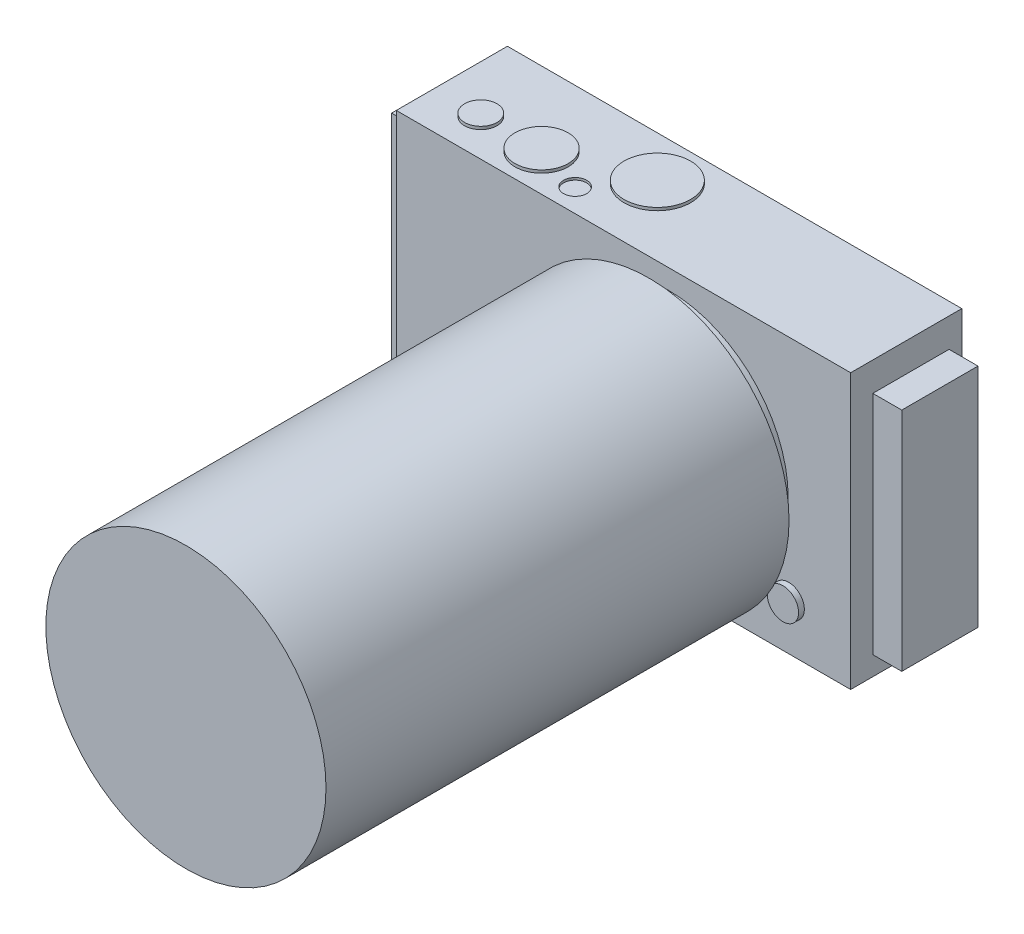
SolidWorks part; units mm, degrees
ref_plane "Front Plane" through (0, 0, 0) normal (0, 0, 1) x (1, 0, 0)
ref_plane "Top Plane" through (0, 0, 0) normal (0, 1, 0) x (1, 0, 0)
ref_plane "Right Plane" through (0, 0, 0) normal (1, 0, 0) x (0, 0, -1)
sketch "Sketch1" plane through (0, 0, 0) normal (0, 0, 1) x (1, 0, 0)
  line L1 (0, 0) -> (99.695, 0)
  line L2 (0, 0) -> (0, 60.198)
  line L3 (0, 60.198) -> (99.695, 60.198)
  line L4 (99.695, 0) -> (99.695, 60.198)
  dimension "D1" = 99.695
  dimension "D2" = 60.198
extrude "Boss-Extrude1" add sketch "Sketch1" along normal blind 24.384
sketch "Sketch2" plane through (0, 0, 24.384) normal (0, 0, 1) x (1, 0, 0)
  line L0 (0, 30.099) -> (99.695, 30.099) construction
  line L1 (0, 60.198) -> (0, 0) construction
  line L2 (99.695, 0) -> (99.695, 60.198) construction
  line L3 (59.7588, 55.88) -> (59.7588, 3.429) construction
  line L4 (99.695, 60.198) -> (0, 60.198) construction
  line L5 (0, 0) -> (99.695, 0) construction
  circle A0 centre (59.7588, 29.6545) radius 26.2255
  point P15 (85.979, 30.1802)
  dimension "D1" = 4.318
  dimension "D2" = 3.429
  dimension "D3" = 13.716
extrude "Boss-Extrude2" add sketch "Sketch2" along normal blind 4.318
sketch "Sketch3" plane through (0, 0, 24.384) normal (0, 0, 1) x (1, 0, 0)
  line L0 (99.695, 0) -> (99.695, 60.198) construction
  line L1 (0, 0) -> (99.695, 0) construction
  circle A0 centre (86.106, 10.16) radius 3.429
  dimension "D1" = 6.858
  dimension "D2" = 13.589
  dimension "D3" = 10.16
extrude "Boss-Extrude3" add sketch "Sketch3" along normal blind 1.27
sketch "Sketch4" plane through (0, 60.198, 0) normal (0, 1, 0) x (1, 0, 0)
  line L0 (0, -24.384) -> (0, 0) construction
  line L1 (99.695, -24.384) -> (0, -24.384) construction
  circle A0 centre (10.414, -16.256) radius 3.556
  circle A1 centre (23.749, -16.256) radius 5.842
  circle A2 centre (42.545, -9.652) radius 7.3025
  dimension "D1" = 7.112
  dimension "D2" = 11.684
  dimension "D3" = 14.605
  dimension "D4" = 10.414
  dimension "D5" = 23.749
  dimension "D6" = 42.545
  dimension "D7" = 8.128
  dimension "D8" = 8.128
  dimension "D9" = 14.732
extrude "Boss-Extrude4" add sketch "Sketch4" along normal blind 0.635
sketch "Sketch7" plane through (0, 60.198, 0) normal (0, 1, 0) x (1, 0, 0)
  line L0 (99.695, -24.384) -> (0, -24.384) construction
  line L1 (0, -24.384) -> (0, 0) construction
  circle A0 centre (34.163, -19.304) radius 2.54
  dimension "D1" = 5.08
  dimension "D2" = 5.08
  dimension "D3" = 34.163
extrude "Cut-Extrude1" cut sketch "Sketch7" against normal blind 0.508
sketch "Sketch8" plane through (0, 0, 0) normal (0, -1, 0) x (1, 0, 0)
  line L0 (99.695, 24.384) -> (99.695, 0) construction
  line L1 (0, 24.384) -> (99.695, 24.384) construction
  circle A0 centre (60.325, 14.224) radius 3.175
  dimension "D3" = 6.35
  dimension "D1" = 39.37
  dimension "D2" = 10.16
extrude "Cut-Extrude2" cut sketch "Sketch8" against normal blind 6.604 contours A0
sketch "Sketch9" plane through (0, 0, 0) normal (-1, 0, 0) x (0, 0, 1)
  line L0 (0, 60.198) -> (0, 0) construction
  line L1 (8.89, 53.848) -> (19.05, 53.848)
  line L2 (8.89, 53.848) -> (8.89, 2.032)
  line L3 (8.89, 2.032) -> (19.05, 2.032)
  line L4 (19.05, 53.848) -> (19.05, 2.032)
  line L5 (24.384, 60.198) -> (0, 60.198) construction
  line L6 (24.384, 0) -> (0, 0) construction
  dimension "D1" = 19.05
  dimension "D2" = 6.35
  dimension "D3" = 2.032
  dimension "D4" = 8.89
extrude "Boss-Extrude5" add sketch "Sketch9" along normal blind 6.35
sketch "Sketch10" plane through (99.695, 0, 0) normal (1, 0, 0) x (0, 0, -1)
  line L0 (0, 0) -> (0, 60.198) construction
  line L1 (-19.5204, 53.848) -> (-2.794, 53.848)
  line L2 (-19.5204, 53.848) -> (-19.5204, 4.191)
  line L3 (-19.5204, 4.191) -> (-2.794, 4.191)
  line L4 (-2.794, 53.848) -> (-2.794, 4.191)
  line L5 (-24.384, 60.198) -> (0, 60.198) construction
  line L6 (-24.384, 0) -> (0, 0) construction
  dimension "D1" = 19.5204
  dimension "D2" = 6.35
  dimension "D3" = 4.191
  dimension "D4" = 2.794
extrude "Boss-Extrude6" add sketch "Sketch10" along normal blind 6.35
sketch "Sketch11" plane through (0, 0, 28.702) normal (0, 0, 1) x (1, 0, 0)
  circle A0 centre (59.7588, 29.6545) radius 30.734
  dimension "D1" = 61.468
extrude "Boss-Extrude7" add sketch "Sketch11" along normal blind 101.6 contours A0
